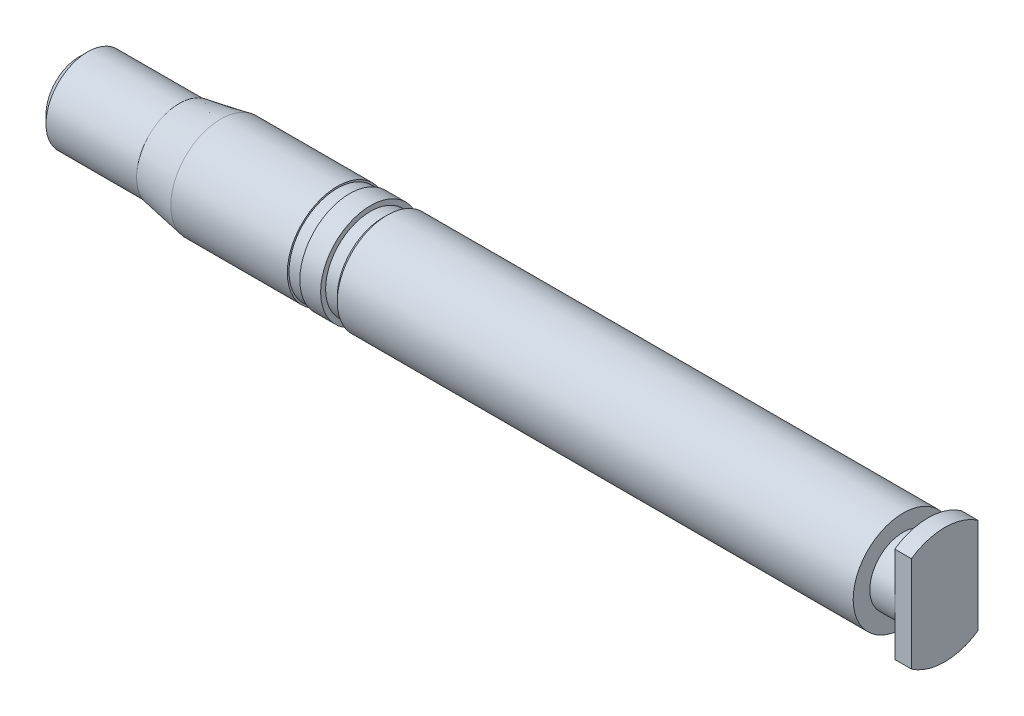
SolidWorks part; units mm, degrees
ref_plane "Plan de face" through (0, 0, 0) normal (0, 0, 1) x (1, 0, 0)
ref_plane "Plan de dessus" through (0, 0, 0) normal (0, 1, 0) x (1, 0, 0)
ref_plane "Plan de droite" through (0, 0, 0) normal (1, 0, 0) x (0, 0, -1)
sketch "Esquisse1" plane through (0, 0, 0) normal (0, 0, 1) x (1, 0, 0)
  line L0 (0, 0) -> (90.0796, 0) construction
  line L1 (0, 0) -> (0, 5)
  line L2 (0, 5) -> (12, 5)
  line L3 (12, 5) -> (12, 5.1184)
  line L4 (12, 5.1184) -> (17, 6)
  line L5 (17, 6) -> (31, 6)
  line L6 (31, 6) -> (31, 5.8)
  line L7 (31, 5.8) -> (32.5, 5.8)
  line L8 (32.5, 5.8) -> (32.5, 6)
  line L9 (32.5, 6) -> (35, 6)
  line L10 (35, 6) -> (35, 5.4)
  line L11 (35, 5.4) -> (36.5, 5.4)
  line L12 (36.5, 5.4) -> (36.5, 6)
  line L13 (36.5, 6) -> (99, 6)
  line L14 (99, 6) -> (99, 4)
  line L15 (99, 4) -> (102, 4)
  line L16 (102, 4) -> (102, 7)
  line L17 (102, 7) -> (104, 7)
  line L18 (104, 7) -> (104, 0)
  line L19 (104, 0) -> (103.3308, 0)
  line L20 (103.3308, 0) -> (0, 0)
  dimension "D1" = 5
  dimension "D2" = 5
  dimension "D3" = 6
  dimension "D4" = 12
  dimension "D5" = 10
  dimension "D6" = 1.5
  dimension "D7" = 5.8
  dimension "D8" = 6
  dimension "D9" = 2.5
  dimension "D10" = 5.4
  dimension "D11" = 1.5
  dimension "D12" = 6
  dimension "D13" = 4
  dimension "D14" = 7
  dimension "D15" = 3
  dimension "D16" = 2
  dimension "D17" = 64
  dimension "D18" = 23
revolve "Révolution1" add sketch "Esquisse1" angle 360 about L0
cosmetic thread "Représentation de filetage2" parameters "D2"=8.5
chamfer "Chanfrein1" distance 1 angle 45 1 edges at (0, 0, 5)
chamfer "Chanfrein2" distance 0.5 angle 45 1 edges at (36.5, 0, 6)
sketch "Esquisse2" plane through (104, 0, 0) normal (1, 0, 0) x (0, 0, -1)
  line L0 (0, 7.5482) -> (0, -7.4621) construction
  line L1 (-4, 7.5482) -> (-4, -7.7204)
  line L2 (4, 7.5482) -> (9.1374, 7.5482)
  line L3 (4, 7.5482) -> (4, -7.7204)
  line L4 (4, -7.7204) -> (9.1374, -7.7204)
  line L5 (9.1374, 7.5482) -> (9.1374, -7.7204)
  line L6 (-4, 7.5482) -> (-9.1374, 7.5482)
  line L7 (-9.1374, 7.5482) -> (-9.1374, -7.7204)
  line L8 (-4, -7.7204) -> (-9.1374, -7.7204)
  dimension "D1" = 8
extrude "Enlèv. mat.-Extru.1" cut sketch "Esquisse2" against normal up to next
ref_plane "Plan1" [suppressed] through (80, 0, 0) normal (1, 0, 0) x (0, 0, -1)
sketch "Esquisse3" [suppressed] plane through (80, 0, 0) normal (1, 0, 0) x (0, 0, -1)
  circle A0 centre (0, 0) radius 8.4944
extrude "Enlèv. mat.-Extru.2" [suppressed] cut sketch "Esquisse3" against normal through all
